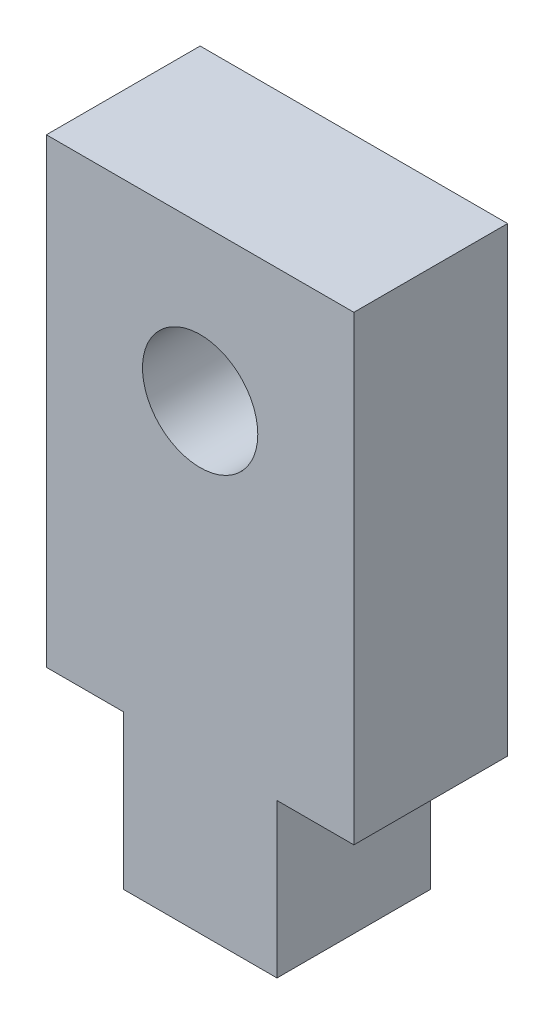
SolidWorks part; units mm, degrees
ref_plane "Front Plane" through (0, 0, 0) normal (0, 0, 1) x (1, 0, 0)
ref_plane "Top Plane" through (0, 0, 0) normal (0, 1, 0) x (1, 0, 0)
ref_plane "Right Plane" through (0, 0, 0) normal (1, 0, 0) x (0, 0, -1)
sketch "Sketch1" plane through (0, 0, 0) normal (0, 0, 1) x (1, 0, 0)
  line L0 (2.5, -7.5) -> (5, -7.5)
  line L1 (-5, 7.5) -> (5, 7.5)
  line L2 (-5, 7.5) -> (-5, -7.5)
  line L3 (-5, -7.5) -> (-2.5, -7.5)
  line L4 (5, 7.5) -> (5, -7.5)
  line L7 (-2.5, -12.5) -> (2.5, -12.5)
  line L8 (-2.5, -12.5) -> (-2.5, -7.5)
  line L10 (2.5, -12.5) -> (2.5, -7.5)
  circle A0 centre (0, 2.5) radius 1.875
  point P0 (0, 0)
  point P5 (0, -7.5)
  dimension "D3" = 5
  dimension "D4" = 3.75
  dimension "D1" = 15
  dimension "D2" = 10
  dimension "D5" = 5
extrude "Boss-Extrude1" add sketch "Sketch1" along normal blind 5
